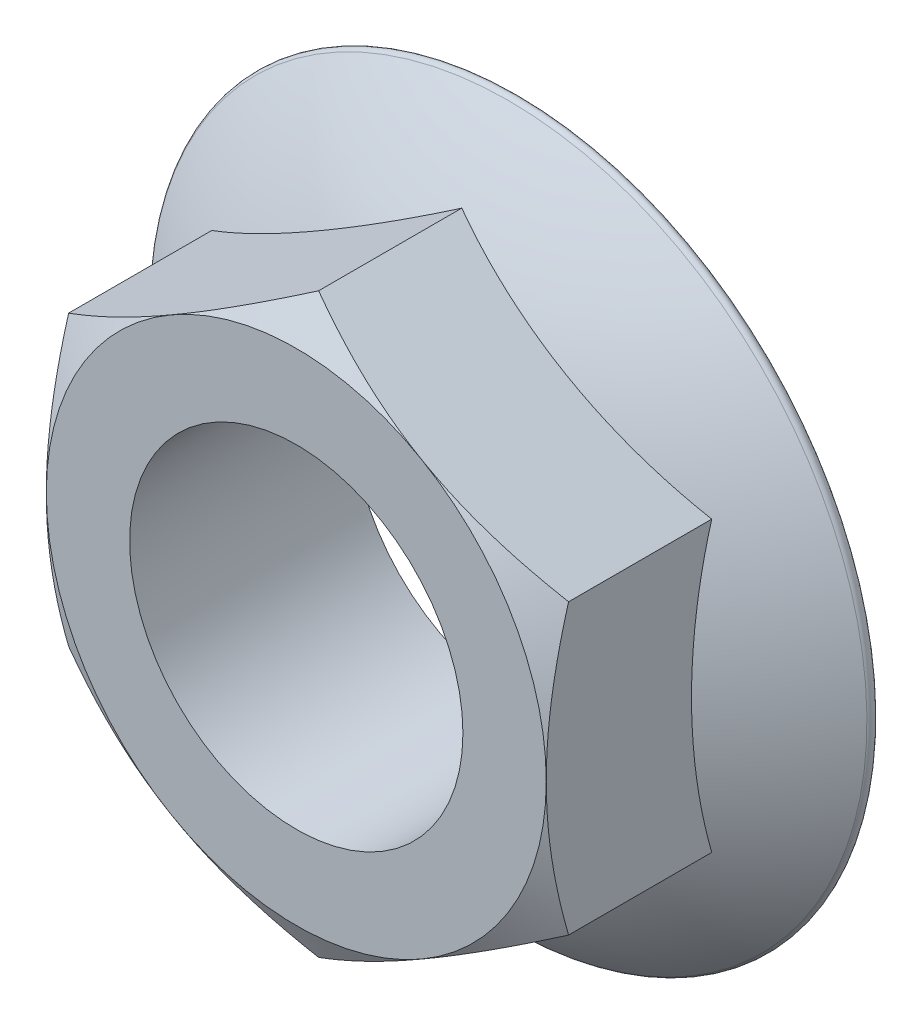
SolidWorks part; units mm, degrees
ref_plane "Front Plane" through (0, 0, 0) normal (0, 0, 1) x (1, 0, 0)
ref_plane "Top Plane" through (0, 0, 0) normal (0, 1, 0) x (1, 0, 0)
ref_plane "Right Plane" through (0, 0, 0) normal (1, 0, 0) x (0, 0, -1)
sketch "Sketch1" plane through (0, 0, 0) normal (0, 0, 1) x (1, 0, 0)
  line L1 (-22.5, 12.9904) -> (-22.5, -12.9904)
  line L2 (-22.5, -12.9904) -> (0, -25.9808)
  line L3 (0, -25.9808) -> (22.5, -12.9904)
  line L4 (22.5, -12.9904) -> (22.5, 12.9904)
  line L5 (22.5, 12.9904) -> (0, 25.9808)
  line L6 (0, 25.9808) -> (-22.5, 12.9904)
  circle A0 centre (0, 0) radius 22.5 construction
  dimension "D1" = 45
extrude "Boss-Extrude1" add sketch "Sketch1" along normal blind 20
sketch "Sketch2" plane through (0, 0, 0) normal (1, 0, 0) x (0, 0, -1)
  line L0 (0, 0) -> (-12, 0)
  line L1 (0, -31.95) -> (0, 0)
  arc A0 (-12, 0) -> (-0.894, -32.2578) centre (40.4001, 0) ccw
  arc A1 (-0.894, -32.2578) -> (0, -31.95) centre (-0.5, -31.95) ccw
  dimension "D2" = 0.5
  dimension "D1" = 12
  dimension "D3" = 31.95
revolve "Revolve1" add sketch "Sketch2" angle 360 about L0
sketch "Sketch3" plane through (0, 0, 20) normal (0, 0, 1) x (1, 0, 0)
  circle A0 centre (0, 0) radius 22.5
extrude "Cut-Extrude1" cut sketch "Sketch3" against normal through all draft 60 flip side to cut
sketch "Sketch4" plane through (0, 0, 20) normal (0, 0, 1) x (1, 0, 0)
  circle A0 centre (0, 0) radius 15
extrude "Cut-Extrude2" cut sketch "Sketch4" against normal through all
cosmetic thread "Cosmetic Thread1" parameters "D2"=31.75
